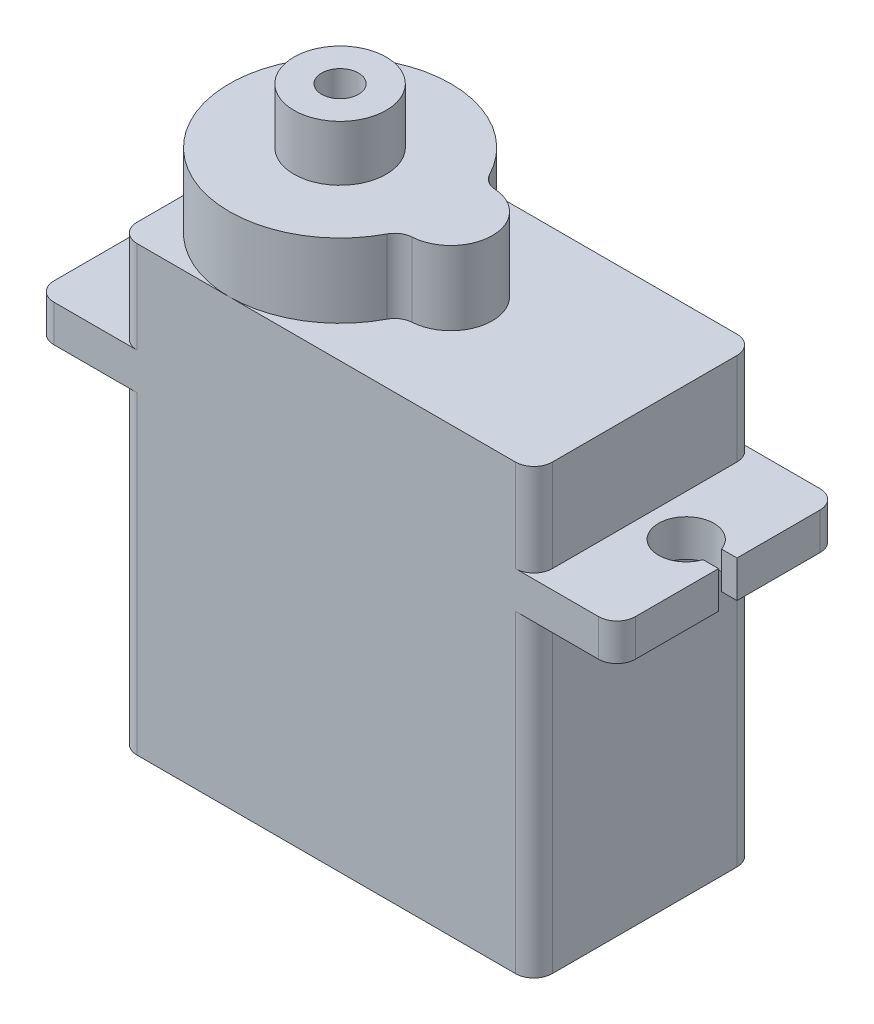
SolidWorks part; units mm, degrees
ref_plane "前视基准面" through (0, 0, 0) normal (0, 0, 1) x (1, 0, 0)
ref_plane "上视基准面" through (0, 0, 0) normal (0, 1, 0) x (1, 0, 0)
ref_plane "右视基准面" through (0, 0, 0) normal (1, 0, 0) x (0, 0, -1)
other "Configuration Table"
sketch "草图1" plane through (0, 0, 0) normal (0, 0, 1) x (1, 0, 0)
  line L0 (0, -12) -> (0, 12) construction
  line L1 (-11.25, -12) -> (11.25, -12)
  line L2 (-11.25, -12) -> (-11.25, 5)
  line L3 (-11.25, 12) -> (11.25, 12)
  line L4 (11.25, -12) -> (11.25, 5)
  line L5 (-11.25, -12) -> (11.25, 12) construction
  line L6 (-11.25, 12) -> (11.25, -12) construction
  line L7 (-11.25, 7) -> (-11.25, 12)
  line L8 (-15.75, 7) -> (-11.25, 7)
  line L9 (-15.75, 7) -> (-15.75, 5)
  line L10 (-15.75, 5) -> (-11.25, 5)
  line L12 (15.75, 5) -> (11.25, 5)
  line L13 (15.75, 7) -> (15.75, 5)
  line L14 (15.75, 7) -> (11.25, 7)
  line L15 (11.25, 7) -> (11.25, 12)
  point P0 (0, 0)
  dimension "D1" = 22.5
  dimension "D2" = 24
  dimension "D3" = 17
  dimension "D4" = 4.5
  dimension "D5" = 2
extrude "凸台-拉伸1" add sketch "草图1" along normal blind 12
sketch "草图2" plane through (0, 12, 0) normal (0, 1, 0) x (1, 0, 0)
  line L0 (11.25, 0) -> (-11.25, 0) construction
  line L1 (11.25, -12) -> (-11.25, -12) construction
  line L2 (-11.25, -12) -> (-11.25, 0) construction
  arc A0 (0.3281, -3.7899) -> (0.3281, -8.2101) centre (-5.25, -6) ccw
  arc A1 (0.3281, -8.2101) -> (0.3281, -3.7899) centre (0.75, -6) ccw
  dimension "D1" = 4.5
  dimension "D2" = 12
extrude "凸台-拉伸2" add sketch "草图2" along normal blind 4
sketch "草图3" plane through (0, 7, 0) normal (0, 1, 0) x (1, 0, 0)
  line L0 (0, 0) -> (0, -12) construction
  line L1 (11.25, -12) -> (-5.25, -12) construction
  line L2 (-15.75, -12) -> (-15.75, 0) construction
  line L4 (-11.25, -12) -> (-15.75, -12) construction
  line L5 (15.75, -6.5) -> (14.9142, -6.5)
  line L6 (-15.75, -5.5) -> (-14.9142, -5.5)
  line L7 (-15.75, -5.5) -> (-15.75, -6.5)
  line L8 (-15.75, -6.5) -> (-14.9142, -6.5)
  line L10 (15.75, -5.5) -> (15.75, -6.5)
  line L11 (15.75, -5.5) -> (14.9142, -5.5)
  arc A0 (-14.9142, -6.5) -> (-14.9142, -5.5) centre (-13.5, -6) ccw
  arc A1 (14.9142, -6.5) -> (14.9142, -5.5) centre (13.5, -6) cw
  point P11 (-15.75, -6)
  point P16 (-13.5, -12)
  dimension "D1" = 3
  dimension "D2" = 1
  dimension "D3" = 0.8358
extrude "切除-拉伸1" cut sketch "草图3" against normal through all
sketch "草图4" plane through (0, 16, 0) normal (0, 1, 0) x (1, 0, 0)
  circle A0 centre (-5.25, -6) radius 2.5
  arc A1 (0.3281, -3.7899) -> (-5.25, 0) centre (-5.25, -6) ccw construction
  dimension "D1" = 5
extrude "凸台-拉伸3" add sketch "草图4" along normal blind 3
fillet "圆角1" radius 1 4 edges at (15.75, 6, 0) (15.75, 6, 12) (-15.75, 6, 0) (-15.75, 6, 12)
fillet "圆角2" radius 1 8 edges at (11.25, -3.5, 0) (11.25, 9.5, 0) (11.25, -3.5, 12) (-11.25, -3.5, 12) (-11.25, -3.5, 0) (11.25, 9.5, 12) (-11.25, 9.5, 0) (-11.25, 9.5, 12)
fillet "圆角3" radius 1 2 edges at (0.3281, 14, 8.2101) (0.3281, 14, 3.7899)
sketch "草图5" plane through (0, 19, 0) normal (0, 1, 0) x (1, 0, 0)
  circle A0 centre (-5.25, -6) radius 1
  circle A1 centre (-5.25, -6) radius 2.5 construction
  dimension "D1" = 2
extrude "切除-拉伸2" cut sketch "草图5" against normal blind 3
sketch "草图6" plane through (0, -12, 0) normal (0, -1, 0) x (1, 0, 0)
  line L0 (-11.25, 11) -> (-11.25, 1) construction
  line L1 (-11.25, 7.5) -> (-10.25, 7.5)
  line L2 (-11.25, 7.5) -> (-11.25, 4.5)
  line L3 (-11.25, 4.5) -> (-10.25, 4.5)
  line L4 (-10.25, 7.5) -> (-10.25, 4.5)
  line L5 (-11.25, 11) -> (-11.25, 1) construction
  point P6 (-11.25, 6)
  dimension "D1" = 3
  dimension "D2" = 1
extrude "切除-拉伸3" cut sketch "草图6" against normal blind 4.5
